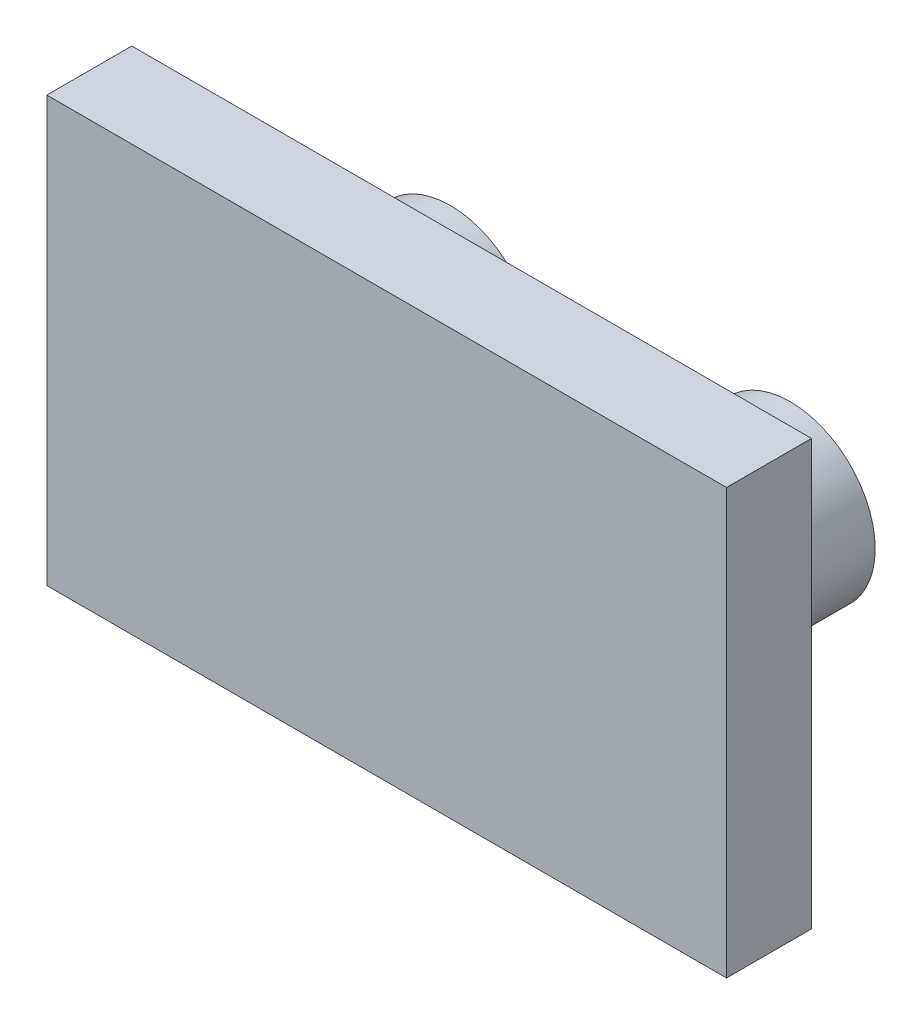
SolidWorks part; units mm, degrees
ref_plane "前视基准面" through (0, 0, 0) normal (0, 0, 1) x (1, 0, 0)
ref_plane "上视基准面" through (0, 0, 0) normal (0, 1, 0) x (1, 0, 0)
ref_plane "右视基准面" through (0, 0, 0) normal (1, 0, 0) x (0, 0, -1)
other "Configuration Table"
sketch "草图1" plane through (0, 0, 0) normal (0, 0, 1) x (1, 0, 0)
  line L1 (-166.2094, 100.003) -> (-6.2094, 100.003)
  line L2 (-166.2094, 100.003) -> (-166.2094, 0.003)
  line L3 (-166.2094, 0.003) -> (-6.2094, 0.003)
  line L4 (-6.2094, 100.003) -> (-6.2094, 0.003)
  point P0 (0, 0)
  dimension "D4" = 100
  dimension "D5" = 160
extrude "凸台-拉伸4" add sketch "草图1" against normal blind 20
sketch "草图3" plane through (0, 0, -20) normal (0, 0, -1) x (-1, 0, 0)
  line L0 (6.2094, 0.003) -> (6.2094, 100.003) construction
  line L1 (166.2094, 0.003) -> (6.2094, 0.003) construction
  circle A0 centre (46.2094, 50.003) radius 20
  circle A1 centre (126.2094, 50.003) radius 20
  point P6 (0, 0)
  point P8 (33.9814, 59.8514)
  point P9 (50.3742, 56.4203)
  point P11 (0, 0)
  dimension "D3" = 40
  dimension "D4" = 40
  dimension "D1" = 40
  dimension "D2" = 50
  dimension "D5" = 80
extrude "凸台-拉伸5" add sketch "草图3" along normal blind 35 contours A1 | A0
